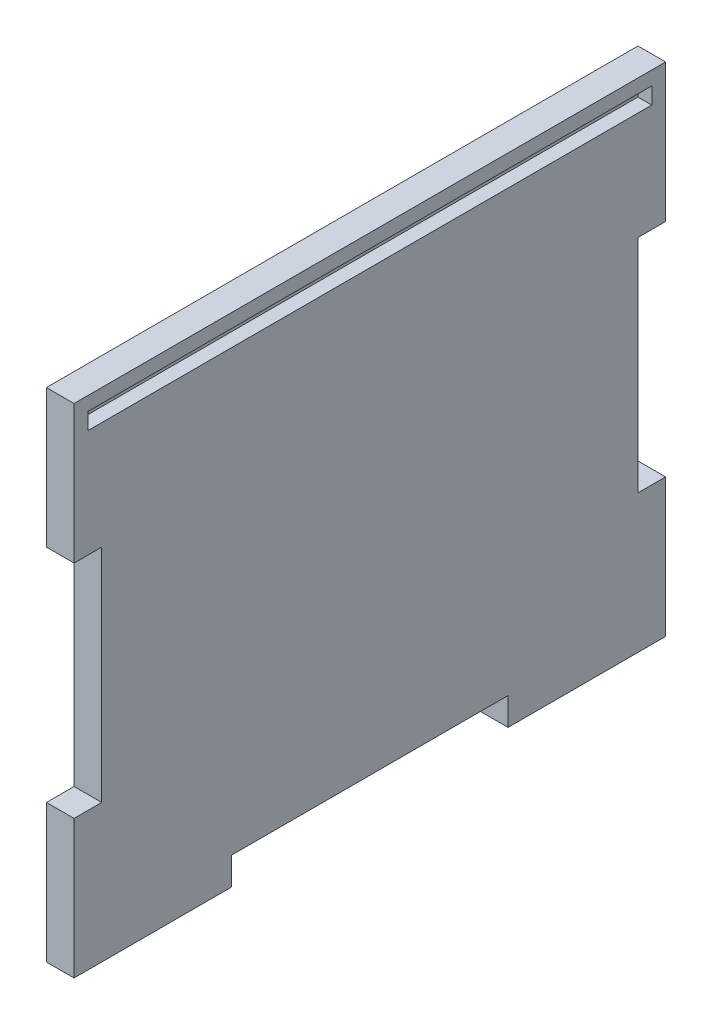
SolidWorks part; units mm, degrees
ref_plane "Front Plane" through (0, 0, 0) normal (0, 0, 1) x (1, 0, 0)
ref_plane "Top Plane" through (0, 0, 0) normal (0, 1, 0) x (1, 0, 0)
ref_plane "Right Plane" through (0, 0, 0) normal (1, 0, 0) x (0, 0, -1)
sketch "Sketch1" plane through (0, 0, 0) normal (1, 0, 0) x (0, 0, -1)
  line L1 (0, 0) -> (107, 0)
  line L2 (0, 0) -> (0, 90)
  line L3 (0, 90) -> (107, 90)
  line L4 (107, 0) -> (107, 90)
  dimension "D1" = 107
  dimension "D2" = 90
extrude "Boss-Extrude1" add sketch "Sketch1" along normal blind 5
sketch "Sketch5" plane through (5, 0, 0) normal (1, 0, 0) x (0, 0, -1)
  line L0 (0, 90) -> (0, 0) construction
  line L1 (0, 65) -> (5, 65)
  line L2 (0, 65) -> (0, 25)
  line L3 (0, 25) -> (5, 25)
  line L4 (5, 65) -> (5, 25)
  line L5 (0, 0) -> (107, 0) construction
  dimension "D1" = 5
  dimension "D2" = 40
  dimension "D3" = 25
extrude "Cut-Extrude2" cut sketch "Sketch5" against normal through all
sketch "Sketch6" plane through (5, 0, 0) normal (1, 0, 0) x (0, 0, -1)
  line L0 (107, 0) -> (107, 90) construction
  line L1 (107, 65) -> (102, 65)
  line L2 (107, 65) -> (107, 25)
  line L3 (107, 25) -> (102, 25)
  line L4 (102, 65) -> (102, 25)
  line L5 (0, 0) -> (107, 0) construction
  dimension "D1" = 40
  dimension "D2" = 5
  dimension "D3" = 25
extrude "Cut-Extrude3" cut sketch "Sketch6" against normal through all
sketch "Sketch7" plane through (5, 0, 0) normal (1, 0, 0) x (0, 0, -1)
  line L0 (0, 0) -> (107, 0) construction
  line L1 (28.5, 0) -> (78.5, 0)
  line L2 (28.5, 0) -> (28.5, 5)
  line L3 (28.5, 5) -> (78.5, 5)
  line L4 (78.5, 0) -> (78.5, 5)
  line L5 (107, 0) -> (107, 25) construction
  dimension "D1" = 50
  dimension "D2" = 5
  dimension "D3" = 28.5
extrude "Cut-Extrude4" cut sketch "Sketch7" against normal through all
sketch "Sketch8" plane through (5, 0, 0) normal (1, 0, 0) x (0, 0, -1)
  line L0 (107, 90) -> (0, 90) construction
  line L1 (2.5, 87.5) -> (104.5, 87.5)
  line L2 (2.5, 87.5) -> (2.5, 84.5)
  line L3 (2.5, 84.5) -> (104.5, 84.5)
  line L4 (104.5, 87.5) -> (104.5, 84.5)
  line L5 (0, 90) -> (0, 65) construction
  dimension "D1" = 102
  dimension "D2" = 3
  dimension "D3" = 2.5
  dimension "D4" = 2.5
extrude "Cut-Extrude5" cut sketch "Sketch8" against normal blind 2.5
